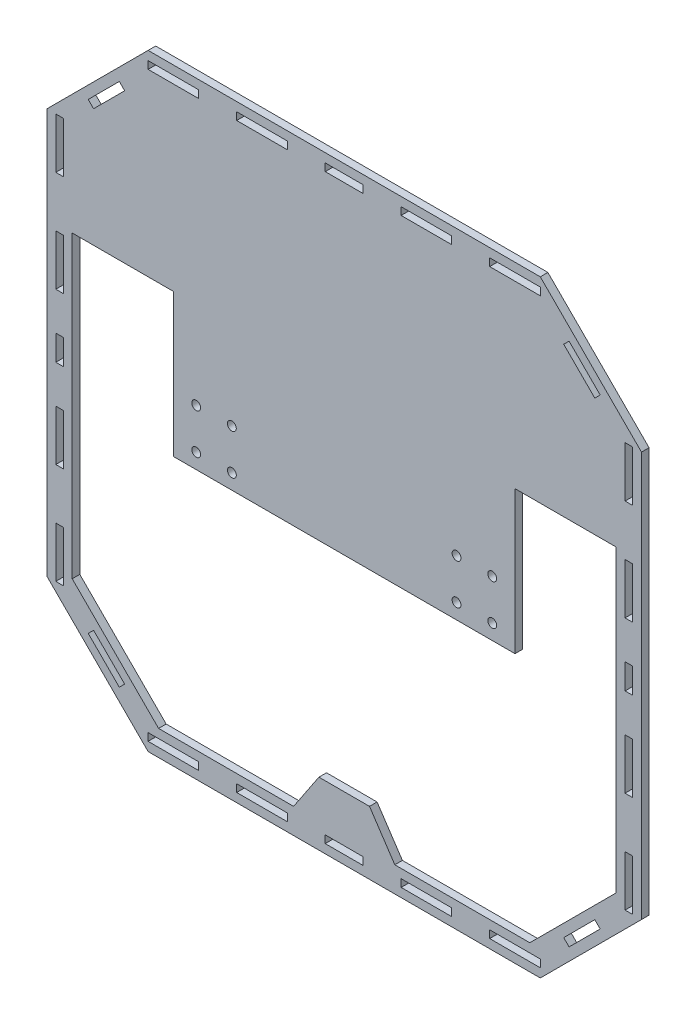
SolidWorks part; units mm, degrees
ref_plane "Přední rovina" through (0, 0, 0) normal (0, 0, 1) x (1, 0, 0)
ref_plane "Horní rovina" through (0, 0, 0) normal (0, 1, 0) x (1, 0, 0)
ref_plane "Pravá rovina" through (0, 0, 0) normal (1, 0, 0) x (0, 0, -1)
sketch "Skica2" plane through (0, 0, 0) normal (0, 0, 1) x (1, 0, 0)
  line L0 (-117.5, 80) -> (-77.5, 120)
  line L1 (-77.5, 120) -> (77.5, 120)
  line L2 (-117.5, 80) -> (-117.5, -80)
  line L3 (-77.5, -120) -> (77.5, -120)
  line L4 (117.5, 80) -> (117.5, -80)
  line L5 (-117.5, 120) -> (117.5, -120) construction
  line L6 (-117.5, -120) -> (117.5, 120) construction
  line L7 (77.5, 120) -> (117.5, 80)
  line L8 (77.5, -120) -> (117.5, -80)
  line L9 (-117.5, -80) -> (-77.5, -120)
  line L10 (0, 120) -> (0, -120) construction
  line L11 (-117.5, 0) -> (122.5, 0) construction
  line L12 (-107.5, -42.5) -> (-107.5, 42.5)
  line L13 (-107.5, 42.5) -> (-67.5, 42.5)
  line L14 (-67.5, 42.5) -> (-67.5, -14)
  line L17 (67.5, 42.5) -> (67.5, -14)
  line L18 (107.5, 42.5) -> (67.5, 42.5)
  line L19 (107.5, -42.5) -> (107.5, 42.5)
  line L20 (58.5, 8) -> (44.4, 8) construction
  line L21 (-111, 60) -> (-114, 60)
  line L22 (-114, 80) -> (-111, 80)
  line L23 (-114, 80) -> (-114, 60)
  line L25 (-111, 80) -> (-111, 60)
  line L26 (-114, 40) -> (-111, 40)
  line L27 (-114, 20) -> (-111, 20)
  line L28 (-114, 5) -> (-111, 5)
  line L29 (-111, 40) -> (-111, 20)
  line L30 (-114, 40) -> (-114, 20)
  line L31 (-111, 5) -> (-111, -5)
  line L32 (-114, 5) -> (-114, -5)
  line L33 (-114, -5) -> (-111, -5)
  line L34 (-114, -40) -> (-114, -20)
  line L35 (-114, -20) -> (-111, -20)
  line L36 (-111, -40) -> (-111, -20)
  line L37 (-114, -40) -> (-111, -40)
  line L38 (-114, -80) -> (-114, -60)
  line L39 (-111, -60) -> (-114, -60)
  line L40 (-111, -80) -> (-111, -60)
  line L41 (-114, -80) -> (-111, -80)
  line L42 (114, -80) -> (111, -80)
  line L43 (111, -80) -> (111, -60)
  line L44 (111, -60) -> (114, -60)
  line L45 (114, -80) -> (114, -60)
  line L46 (114, -40) -> (111, -40)
  line L47 (111, -40) -> (111, -20)
  line L48 (114, -20) -> (111, -20)
  line L49 (114, -40) -> (114, -20)
  line L50 (114, 5) -> (111, 5)
  line L51 (111, 5) -> (111, -5)
  line L52 (114, -5) -> (111, -5)
  line L53 (114, 5) -> (114, -5)
  line L54 (114, 40) -> (114, 20)
  line L55 (114, 20) -> (111, 20)
  line L56 (111, 40) -> (111, 20)
  line L57 (114, 40) -> (111, 40)
  line L58 (114, 80) -> (114, 60)
  line L59 (111, 60) -> (114, 60)
  line L60 (111, 80) -> (111, 60)
  line L61 (114, 80) -> (111, 80)
  line L62 (-57.5, 116.5) -> (-57.5, 113.5)
  line L63 (-77.5, 116.5) -> (-57.5, 116.5)
  line L64 (-77.5, 116.5) -> (-77.5, 113.5)
  line L65 (-77.5, 113.5) -> (-57.5, 113.5)
  line L67 (-42.5, 116.5) -> (-42.5, 113.5)
  line L68 (-22.5, 116.5) -> (-22.5, 113.5)
  line L69 (-7.5, 116.5) -> (-7.5, 113.5)
  line L70 (-42.5, 116.5) -> (-22.5, 116.5)
  line L71 (-42.5, 113.5) -> (-22.5, 113.5)
  line L72 (-7.5, 113.5) -> (7.5, 113.5)
  line L73 (-7.5, 116.5) -> (7.5, 116.5)
  line L74 (7.5, 116.5) -> (7.5, 113.5)
  line L75 (42.5, 116.5) -> (22.5, 116.5)
  line L76 (22.5, 116.5) -> (22.5, 113.5)
  line L77 (42.5, 113.5) -> (22.5, 113.5)
  line L78 (42.5, 116.5) -> (42.5, 113.5)
  line L79 (77.5, 116.5) -> (57.5, 116.5)
  line L80 (57.5, 116.5) -> (57.5, 113.5)
  line L81 (77.5, 113.5) -> (57.5, 113.5)
  line L82 (77.5, 116.5) -> (77.5, 113.5)
  line L83 (77.5, -116.5) -> (77.5, -113.5)
  line L84 (77.5, -113.5) -> (57.5, -113.5)
  line L85 (57.5, -116.5) -> (57.5, -113.5)
  line L86 (77.5, -116.5) -> (57.5, -116.5)
  line L87 (42.5, -116.5) -> (42.5, -113.5)
  line L88 (42.5, -113.5) -> (22.5, -113.5)
  line L89 (22.5, -116.5) -> (22.5, -113.5)
  line L90 (42.5, -116.5) -> (22.5, -116.5)
  line L91 (-7.5, -116.5) -> (-7.5, -113.5)
  line L92 (-7.5, -116.5) -> (7.5, -116.5)
  line L93 (7.5, -116.5) -> (7.5, -113.5)
  line L94 (-7.5, -113.5) -> (7.5, -113.5)
  line L95 (-42.5, -116.5) -> (-22.5, -116.5)
  line L96 (-22.5, -116.5) -> (-22.5, -113.5)
  line L97 (-42.5, -113.5) -> (-22.5, -113.5)
  line L98 (-42.5, -116.5) -> (-42.5, -113.5)
  line L99 (-77.5, -116.5) -> (-57.5, -116.5)
  line L100 (-57.5, -116.5) -> (-57.5, -113.5)
  line L101 (-77.5, -113.5) -> (-57.5, -113.5)
  line L102 (-77.5, -116.5) -> (-77.5, -113.5)
  line L103 (101.1685, -91.3817) -> (88.8817, -103.6685)
  line L104 (88.8817, -103.6685) -> (86.7604, -101.5472)
  line L105 (86.7604, -101.5472) -> (99.0472, -89.2604)
  line L106 (99.0472, -89.2604) -> (101.1685, -91.3817)
  line L107 (-86.7604, -101.5472) -> (-99.0472, -89.2604)
  line L108 (-88.8817, -103.6685) -> (-86.7604, -101.5472)
  line L109 (-101.1685, -91.3817) -> (-88.8817, -103.6685)
  line L110 (-99.0472, -89.2604) -> (-101.1685, -91.3817)
  line L111 (86.7604, 101.5472) -> (99.0472, 89.2604)
  line L112 (88.8817, 103.6685) -> (86.7604, 101.5472)
  line L113 (101.1685, 91.3817) -> (88.8817, 103.6685)
  line L114 (99.0472, 89.2604) -> (101.1685, 91.3817)
  line L115 (-88.8817, 103.6685) -> (-86.7604, 101.5472)
  line L116 (-101.1685, 91.3817) -> (-88.8817, 103.6685)
  line L117 (-99.0472, 89.2604) -> (-101.1685, 91.3817)
  line L118 (-86.7604, 101.5472) -> (-99.0472, 89.2604)
  line L119 (-67.5, -14) -> (67.5, -14)
  line L120 (-107.5, -42.5) -> (-107.5, -75.8579)
  line L121 (-107.5, -75.8579) -> (-73.3579, -110)
  line L122 (73.3579, -110) -> (20, -110)
  line L123 (107.5, -42.5) -> (107.5, -75.8579)
  line L124 (107.5, -75.8579) -> (73.3579, -110)
  line L125 (10, -95) -> (-10, -95)
  line L126 (-10, -95) -> (-20, -110)
  line L127 (10, -95) -> (20, -110)
  line L128 (-20, -110) -> (-73.3579, -110)
  circle A0 centre (58.5, 8) radius 1.75
  circle A1 centre (44.4, 8) radius 1.75
  circle A2 centre (44.4, -8) radius 1.75
  circle A3 centre (58.5, -8) radius 1.75
  circle A4 centre (-44.4, -8) radius 1.75
  circle A5 centre (-58.5, -8) radius 1.75
  circle A6 centre (-58.5, 8) radius 1.75
  circle A7 centre (-44.4, 8) radius 1.75
  point P0 (0, 0)
  point P23 (-107.5, 0)
  point P24 (-67.5, 0)
  point P57 (-114, 0)
  point P58 (-111, 0)
  point P101 (0, 113.5)
  point P102 (0, 116.5)
  point P135 (0, -110)
  point P154 (0, -95)
  dimension "D6" = 3.5
  dimension "D7" = 3.5
  dimension "D28" = 10
  dimension "D31" = 10
  dimension "D1" = 235
  dimension "D2" = 240
  dimension "D3" = 40
  dimension "D4" = 85
  dimension "D5" = 10
  dimension "D8" = 14.1
  dimension "D9" = 9
  dimension "D10" = 16
  dimension "D11" = 3
  dimension "D12" = 3.5
  dimension "D17" = 20
  dimension "D18" = 20
  dimension "D19" = 20
  dimension "D20" = 15
  dimension "D21" = 3.5
  dimension "D22" = 3
  dimension "D23" = 20
  dimension "D24" = 15
  dimension "D25" = 20
  dimension "D26" = 15
  dimension "D27" = 14
  dimension "D29" = 10
  dimension "D30" = 49
  dimension "D32" = 15
  dimension "D33" = 3
  dimension "D34" = 3.5
  dimension "D35" = 15
  dimension "D36" = 15
  dimension "D37" = 20
extrude "Přidat vysunutím1" add sketch "Skica2" along normal blind 3
